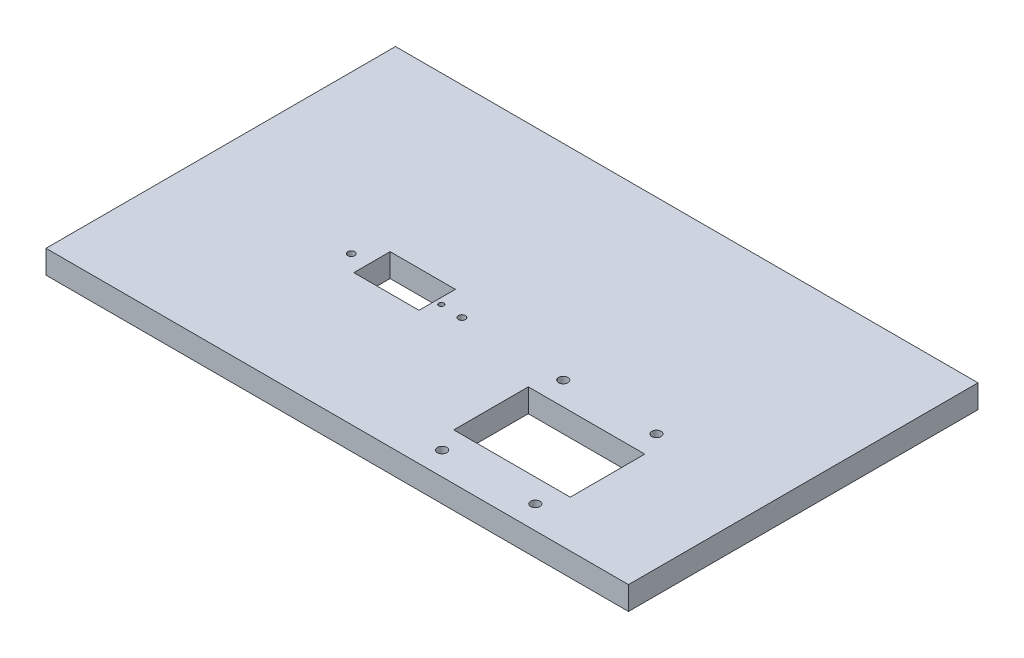
SolidWorks part; units mm, degrees
ref_plane "Front Plane" through (0, 0, 0) normal (0, 0, 1) x (1, 0, 0)
ref_plane "Top Plane" through (0, 0, 0) normal (0, 1, 0) x (1, 0, 0)
ref_plane "Right Plane" through (0, 0, 0) normal (1, 0, 0) x (0, 0, -1)
sketch "Sketch2" plane through (0, 0, 0) normal (0, 1, 0) x (1, 0, 0)
  line L1 (-125, 75) -> (125, 75)
  line L2 (-125, 75) -> (-125, -75)
  line L3 (-125, -75) -> (125, -75)
  line L4 (125, 75) -> (125, -75)
  line L5 (-125, 75) -> (125, -75) construction
  line L6 (-125, -75) -> (125, 75) construction
  point P0 (0, 0)
  dimension "D1" = 250
  dimension "D2" = 150
extrude "Boss-Extrude1" add sketch "Sketch2" along normal blind 10
sketch "Sketch3" plane through (0, 10, 0) normal (0, 1, 0) x (1, 0, 0)
  line L1 (30, -23) -> (80, -23)
  line L2 (30, -23) -> (30, -55)
  line L3 (30, -55) -> (80, -55)
  line L4 (80, -23) -> (80, -55)
  circle A0 centre (35, -13) radius 2
  circle A1 centre (75, -13) radius 2
  circle A2 centre (35, -65) radius 2
  circle A3 centre (75, -65) radius 2
extrude "Cut-Extrude1" cut sketch "Sketch3" against normal blind 10
sketch "Sketch4" plane through (0, 10, 0) normal (0, 1, 0) x (1, 0, 0)
  line L1 (-49.9, -2.4028) -> (-21.9, -2.4028)
  line L2 (-49.9, -2.4028) -> (-49.9, -18)
  line L3 (-49.9, -18) -> (-21.9, -18)
  line L4 (-21.9, -2.4028) -> (-21.9, -18)
  dimension "D1" = 28
extrude "Cut-Extrude2" cut sketch "Sketch4" against normal blind 10
sketch "Sketch5" plane through (0, 10, 0) normal (0, 1, 0) x (1, 0, 0)
  circle A0 centre (-10, -11.5) radius 1.5
  circle A1 centre (-57.5, -11.5) radius 1.5
  circle A2 centre (-19.3, -11.05) radius 1.1
extrude "Cut-Extrude3" cut sketch "Sketch5" against normal through all
